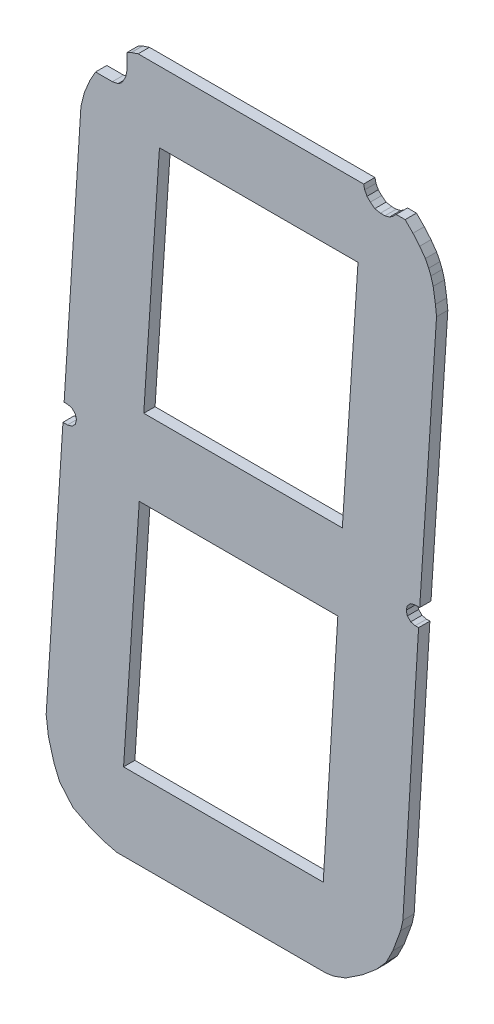
SolidWorks part; units mm, degrees
ref_plane "Ebene vorne" through (0, 0, 0) normal (0, 0, 1) x (1, 0, 0)
ref_plane "Ebene oben" through (0, 0, 0) normal (0, 1, 0) x (1, 0, 0)
ref_plane "Ebene rechts" through (0, 0, 0) normal (1, 0, 0) x (0, 0, -1)
sketch "Skizze1" plane through (0, 0, 0) normal (0, 0, 1) x (1, 0, 0)
  line L0 (13.6525, -5.08) -> (-14.4463, -5.08)
  line L1 (-14.4463, -5.08) -> (-16.6687, -38.735)
  line L2 (-16.6687, -38.735) -> (11.5887, -38.735)
  line L3 (11.5887, -38.735) -> (13.6525, -5.08)
  line L4 (-13.8113, 6.0325) -> (-11.5887, 39.6875)
  line L5 (-11.5887, 39.6875) -> (16.51, 39.6875)
  line L6 (16.51, 39.6875) -> (14.2875, 6.0325)
  line L7 (14.2875, 6.0325) -> (-13.8113, 6.0325)
  line L8 (17.145, -47.3075) -> (19.05, -45.72)
  line L9 (19.05, -45.72) -> (20.4787, -44.1325)
  line L10 (22.86, -37.7825) -> (25.0825, -0.7938)
  line L11 (22.5425, -39.2113) -> (22.86, -37.7825)
  line L12 (21.4313, -42.2275) -> (22.5425, -39.2113)
  line L13 (20.4787, -44.1325) -> (21.4313, -42.2275)
  line L14 (14.7637, -48.895) -> (17.145, -47.3075)
  line L15 (13.0175, -49.53) -> (14.7637, -48.895)
  line L16 (11.9063, -49.6887) -> (13.0175, -49.53)
  line L17 (-17.6213, -49.6887) -> (11.9063, -49.6887)
  line L18 (-26.5113, -43.18) -> (-25.7175, -45.085)
  line L19 (-25.7175, -45.085) -> (-23.8125, -47.3075)
  line L20 (-23.8125, -47.3075) -> (-21.59, -48.4187)
  line L21 (-21.59, -48.4187) -> (-19.5263, -49.2125)
  line L22 (-19.5263, -49.2125) -> (-17.6213, -49.6887)
  line L23 (-27.305, -40.3225) -> (-26.5113, -43.18)
  line L24 (-27.6225, -37.7825) -> (-27.305, -40.3225)
  line L25 (-25.2471, -0.7934) -> (-27.6225, -37.7825)
  line L26 (-22.7013, 39.2112) -> (-25.0825, 1.7462)
  line L27 (-24.6063, 1.7462) -> (-23.9713, 1.5875)
  line L28 (-25.0825, 1.7462) -> (-24.6063, 1.7462)
  line L29 (-23.9713, 1.5875) -> (-23.495, 1.1112)
  line L30 (-23.495, 1.1112) -> (-23.3363, 0.4762)
  line L31 (-23.3363, 0.4762) -> (-23.495, -0.1588)
  line L32 (-23.495, -0.1588) -> (-23.9713, -0.635)
  line L33 (-23.9713, -0.635) -> (-24.6063, -0.7938)
  line L34 (-24.6063, -0.7938) -> (-25.2471, -0.7934)
  line L35 (24.6063, 1.7462) -> (25.2413, 1.7462)
  line L36 (25.2413, 1.7462) -> (27.6225, 38.5762)
  line L37 (23.9713, 1.5875) -> (24.6063, 1.7462)
  line L38 (23.495, 1.1112) -> (23.9713, 1.5875)
  line L39 (23.3363, 0.4762) -> (23.495, 1.1112)
  line L40 (23.495, -0.1588) -> (23.3363, 0.4762)
  line L41 (23.9713, -0.635) -> (23.495, -0.1588)
  line L42 (24.6063, -0.7938) -> (23.9713, -0.635)
  line L43 (25.0825, -0.7938) -> (24.6063, -0.7938)
  line L44 (26.8287, 43.18) -> (26.5113, 43.9737)
  line L45 (27.1463, 42.0687) -> (26.8287, 43.18)
  line L46 (27.4637, 40.005) -> (27.1463, 42.0687)
  line L47 (27.6225, 38.5762) -> (27.4637, 40.005)
  line L48 (24.2888, 47.1487) -> (23.1775, 48.26)
  line L49 (25.2413, 46.0375) -> (24.2888, 47.1487)
  line L50 (26.035, 44.9263) -> (25.2413, 46.0375)
  line L51 (26.5113, 43.9737) -> (26.035, 44.9263)
  line L52 (18.2563, 47.9425) -> (17.78, 48.4187)
  line L53 (18.8913, 47.4662) -> (18.2563, 47.9425)
  line L54 (19.685, 47.3075) -> (18.8913, 47.4662)
  line L55 (20.32, 47.3075) -> (19.685, 47.3075)
  line L56 (20.955, 47.4662) -> (20.32, 47.3075)
  line L57 (21.4313, 47.7837) -> (20.955, 47.4662)
  line L58 (21.9075, 48.26) -> (21.4313, 47.7837)
  line L59 (23.1775, 48.26) -> (21.9075, 48.26)
  line L60 (17.3037, 49.6887) -> (12.7, 49.6887)
  line L61 (17.78, 48.4187) -> (17.4625, 49.0537)
  line L62 (17.4625, 49.0537) -> (17.3037, 49.6887)
  line L63 (12.7, 49.6887) -> (-14.605, 49.6887)
  line L64 (-15.5575, 49.3712) -> (-16.1925, 49.0537)
  line L65 (-14.605, 49.6887) -> (-15.5575, 49.3712)
  line L66 (-18.2563, 44.45) -> (-20.6375, 44.45)
  line L67 (-20.6375, 44.45) -> (-21.4313, 43.0212)
  line L68 (-21.4313, 43.0212) -> (-22.225, 41.1162)
  line L69 (-22.225, 41.1162) -> (-22.7013, 39.2112)
  line L70 (-16.6687, 45.4025) -> (-16.9863, 44.9262)
  line L71 (-16.3513, 46.0375) -> (-16.6687, 45.4025)
  line L72 (-16.1925, 46.8312) -> (-16.3513, 46.0375)
  line L73 (-16.1925, 49.0537) -> (-16.1925, 46.8312)
  line L74 (-16.9863, 44.9262) -> (-17.4625, 44.6087)
  line L75 (-17.4625, 44.6087) -> (-18.2563, 44.45)
extrude "Aufsatz-Linear austragen1" add sketch "Skizze1" along normal blind 1.6
